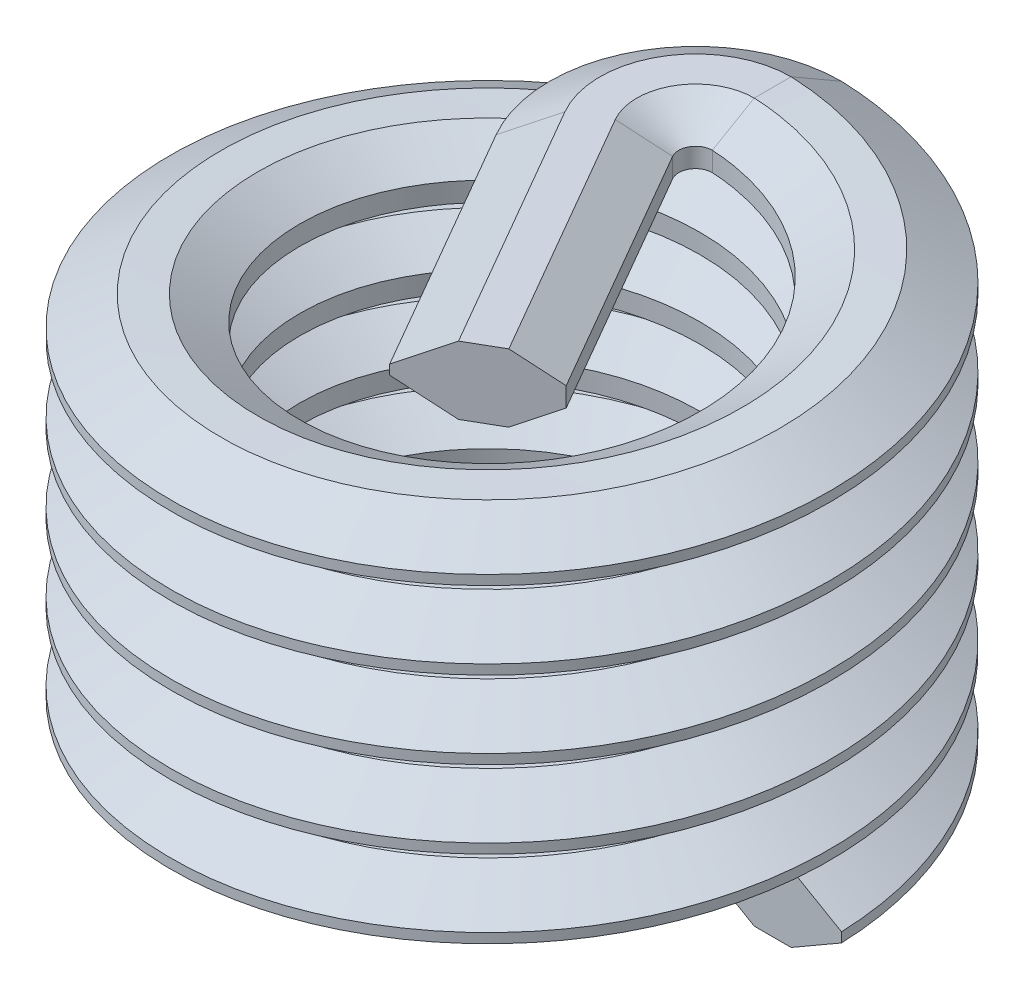
SolidWorks part; units mm, degrees
ref_plane "Front Plane" through (0, 0, 0) normal (0, 0, 1) x (1, 0, 0)
ref_plane "Top Plane" through (0, 0, 0) normal (0, 1, 0) x (1, 0, 0)
ref_plane "Right Plane" through (0, 0, 0) normal (1, 0, 0) x (0, 0, -1)
sketch "Sketch1" plane through (0, 0, 0) normal (0, 0, 1) x (-1, 0, 0)
  line L0 (0, 0) -> (0, 9.525) construction
  line L1 (-1.8938, 0) -> (-2.5866, 0.4) construction
  line L2 (-2.7938, 0.4) -> (-3.4866, 0) construction
  line L3 (-3.4866, 0) -> (-2.7938, -0.4) construction
  line L4 (-2.5866, -0.4) -> (-1.8938, 0) construction
  line L5 (-2.5866, -0.4) -> (-2.5866, 0.4) construction
  line L6 (-1.8938, 0) -> (0, 0) construction
  line L8 (-3.4, -0.05) -> (-2.8804, -0.35)
  line L9 (-2.5, -0.35) -> (-2.067, -0.1)
  line L10 (-1.9804, -0.05) -> (-1.9804, 0.05) construction
  line L11 (-2.067, 0.1) -> (-2.5, 0.35)
  line L12 (-2.8804, 0.35) -> (-3.4, 0.05)
  line L13 (-1.8938, 0) -> (-1.9804, 0) construction
  line L14 (-1.9804, 0) -> (-2.5, 0) construction
  line L15 (-2.8804, 0) -> (-3.4, 0) construction
  line L16 (-3.4, 0) -> (-3.4866, 0) construction
  line L17 (-2.8804, 0.35) -> (-2.5, 0.35)
  line L18 (-2.5, 0.35) -> (-2.5, -0.35) construction
  line L19 (-2.5, -0.35) -> (-2.8804, -0.35)
  line L20 (-2.8804, -0.35) -> (-2.8804, 0.35) construction
  line L21 (-2.8804, 0) -> (-2.5866, 0) construction
  line L22 (-2.5866, 0) -> (-2.5, 0) construction
  line L23 (-3.4, 0.4) -> (-3.4, -4.6) construction
  line L24 (-2.067, -0.1) -> (-2.067, 0.1)
  line L25 (-2.067, 0) -> (-1.9804, 0) construction
  line L26 (-3.4, -0.05) -> (-3.4, 0.05)
  line L28 (3.4, 0.4) -> (3.4, -4.6) construction
  line L29 (-2.5866, -0.4) -> (-2.7938, -0.4) construction
  line L31 (-2.7938, 0.4) -> (-2.5866, 0.4) construction
  dimension "D3" = 0.8
  dimension "D4" = 0.1
  dimension "Installed Length" = 5
  dimension "Thread Size" = 5
  dimension "Max OD" = 6.8
sketch "Sketch2" plane through (0, 0, 0) normal (0, 1, 0) x (1, 0, 0)
  circle A0 centre (0, 0) radius 2.5
curve "Helix/Spiral1" pitch 0.8 height 4.2 turns 5.25 parameters "Height"=4.2, "Pitch"=0.8
sweep "Sweep1" add profiles "Sketch1" path "Helix/Spiral1"
sketch "Sketch3" plane through (0, 0, 0) normal (-1, 0, 0) x (0, 0, 1)
  line L0 (-5.9643, 1.8499) -> (-1.8938, 4.2) construction
  line L1 (-8.3762, 7.9426) -> (-1.8938, 4.2) construction
  line L2 (-1.8938, 4.2) -> (-1.8938, 4.4) construction
  line L8 (-2.5, 3.85) -> (-2.067, 4.1)
  line L9 (-2.067, 4.1) -> (-2.067, 4.3)
  line L10 (-2.067, 4.3) -> (-2.5, 4.55)
  line L12 (-2.8804, 4.55) -> (-3.4, 4.25)
  line L13 (-3.4, 4.25) -> (-3.4, 4.15)
  line L14 (-3.4, 4.15) -> (-2.8804, 3.85)
  line L16 (-2.5, 3.85) -> (-2.067, 4.1)
  line L17 (-2.067, 4.1) -> (-2.067, 4.3)
  line L18 (-2.067, 4.3) -> (-2.5, 4.55)
  line L20 (-2.8804, 4.55) -> (-3.4, 4.25)
  line L21 (-3.4, 4.25) -> (-3.4, 4.15)
  line L22 (-3.4, 4.15) -> (-2.8804, 3.85)
  line L23 (-2.5, 4.55) -> (-2.8804, 4.55)
  line L24 (-2.5, 4.55) -> (-2.8804, 4.55)
  line L25 (-2.8804, 3.85) -> (-2.5, 3.85)
  line L26 (-2.8804, 3.85) -> (-2.5, 3.85)
  dimension "D1" = 0
revolve "Revolve1" add sketch "Sketch3" angle 120 about L2
sketch "Sketch4" plane through (-0.82, 0, -1.4203) normal (0.5, 0, 0.866) x (0.866, 0, -0.5)
  line L8 (-0.0397, 3.85) -> (0.3407, 3.85)
  line L9 (0.3407, 3.85) -> (0.7737, 4.1)
  line L10 (0.7737, 4.1) -> (0.7737, 4.3)
  line L11 (0.7737, 4.3) -> (0.3407, 4.55)
  line L12 (-0.0397, 3.85) -> (0.3407, 3.85)
  line L13 (-0.0397, 4.55) -> (-0.5593, 4.25)
  line L14 (-0.5593, 4.25) -> (-0.5593, 4.15)
  line L15 (-0.5593, 4.15) -> (-0.0397, 3.85)
  line L17 (0.3407, 3.85) -> (0.7737, 4.1)
  line L18 (0.7737, 4.1) -> (0.7737, 4.3)
  line L19 (0.7737, 4.3) -> (0.3407, 4.55)
  line L21 (-0.0397, 4.55) -> (-0.5593, 4.25)
  line L22 (-0.5593, 4.25) -> (-0.5593, 4.15)
  line L23 (-0.5593, 4.15) -> (-0.0397, 3.85)
  spline S4 degree 1 poles (2000.3393, 4.55) (-2000.0324, 4.55) knots -5257.830583 -5257.830583 5258.814998 5258.814998 only from (0.3407, 4.55) to (-0.0397, 4.55)
  spline S5 degree 1 poles (0.3407, 4.55) (-0.0397, 4.55) knots 0 0 1 1
  dimension "D1" = 0
extrude "Extrude1" add sketch "Sketch4" along normal blind 3
equation "\"D3@Sketch1\" = \"Pitch@Helix/Spiral1\""
equation "\"D4@Sketch1\" = \"D3@Sketch1\"  * 1 / 8"
equation "\"D1@Extrude1\" = \"Thread Size@Sketch1\" * 0.6"
equation "\"Height@Helix/Spiral1\" = \"Installed Length@Sketch1\" - \"Pitch@Helix/Spiral1\""
